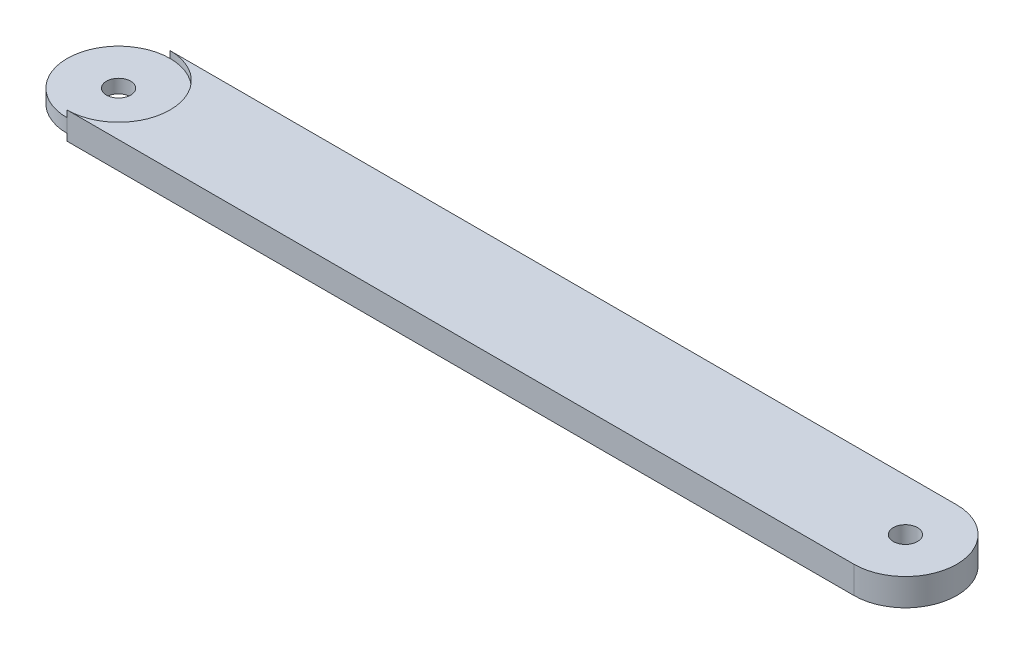
SolidWorks part; units mm, degrees
ref_plane "Plan de face" through (0, 0, 0) normal (0, 0, 1) x (1, 0, 0)
ref_plane "Plan de dessus" through (0, 0, 0) normal (0, 1, 0) x (1, 0, 0)
ref_plane "Plan de droite" through (0, 0, 0) normal (1, 0, 0) x (0, 0, -1)
sketch "Esquisse1" plane through (0, 0, 0) normal (0, 1, 0) x (1, 0, 0)
  line L0 (-232.15, 0) -> (232.15, 0) construction
  line L1 (-232.15, 30.35) -> (232.15, 30.35)
  line L2 (-232.15, -30.35) -> (232.15, -30.35)
  arc A0 (-232.15, 30.35) -> (-232.15, -30.35) centre (-232.15, 0) ccw
  arc A1 (232.15, -30.35) -> (232.15, 30.35) centre (232.15, 0) ccw
  point P2 (0, 0)
  dimension "D1" = 464.3
  dimension "D2" = 60.7
extrude "Boss.-Extru.1" add sketch "Esquisse1" along normal mid plane 16
sketch "Esquisse2" plane through (0, 8, 0) normal (0, 1, 0) x (1, 0, 0)
  circle A0 centre (232.15, 0) radius 7.15
  dimension "D1" = 14.3
extrude "Enlèv. mat.-Extru.1" cut sketch "Esquisse2" against normal through all
sketch "Esquisse3" plane through (0, 8, 0) normal (0, 1, 0) x (1, 0, 0)
  circle A0 centre (-232.15, 0) radius 30.35
  dimension "D1" = 60.7
extrude "Enlèv. mat.-Extru.4" cut sketch "Esquisse3" against normal blind 4
mirror "Symétrie4" about plane through (0, 0, 0) normal (0, 1, 0) of "Enlèv. mat.-Extru.4"
sketch "Esquisse4" plane through (0, 4, 0) normal (0, 1, 0) x (1, 0, 0)
  circle A0 centre (-232.15, 0) radius 7.15
  dimension "D1" = 14.3
extrude "Enlèv. mat.-Extru.5" cut sketch "Esquisse4" against normal through all
